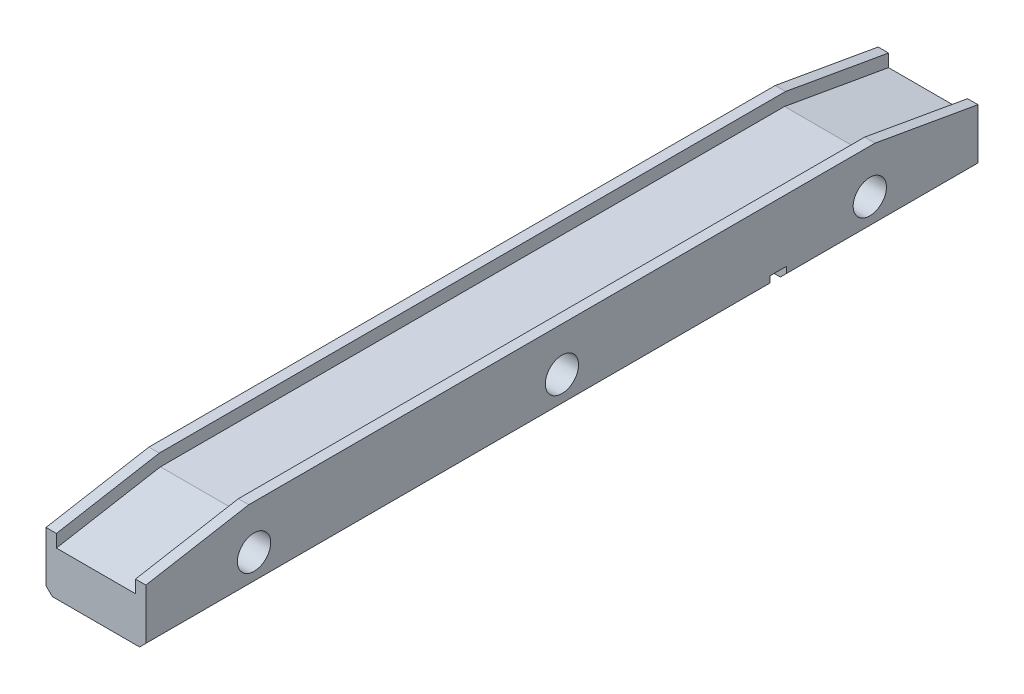
SolidWorks part; units mm, degrees
material "UHMW 15mm"
ref_plane "Plano frontal" through (0, 0, 0) normal (0, 0, 1) x (1, 0, 0)
ref_plane "Plano superior" through (0, 0, 0) normal (0, 1, 0) x (1, 0, 0)
ref_plane "Plano direito" through (0, 0, 0) normal (1, 0, 0) x (0, 0, -1)
sketch "Esboço1" plane through (0, 0, 0) normal (0, 0, 1) x (1, 0, 0)
  line L0 (-19, 0) -> (19, 0)
  line L1 (19, 0) -> (19, 6)
  line L2 (19, 6) -> (24, 6)
  line L3 (24, 6) -> (24, -30)
  line L4 (24, -30) -> (-24, -30)
  line L5 (0, -30) -> (0, 0) construction
  line L6 (-24, 6) -> (-24, -30)
  line L7 (-19, 6) -> (-24, 6)
  line L8 (-19, 0) -> (-19, 6)
  dimension "D1" = 38
  dimension "D2" = 48
  dimension "D3" = 6
  dimension "D4" = 30
extrude "Ressalto-extrusão1" add sketch "Esboço1" along normal mid plane 356
sketch "Esboço2" plane through (24, 0, 0) normal (1, 0, 0) x (0, 0, -1)
  line L0 (-178, -15) -> (178, -15) construction
  line L1 (-178, -30) -> (-178, 6) construction
  line L2 (178, -30) -> (178, 6) construction
  line L4 (-178, -36.6936) -> (-148, -36.6936) construction
  line L5 (-148, -36.6936) -> (-148, -15) construction
  line L6 (148, -15) -> (148, -36.6936) construction
  line L7 (148, -36.6936) -> (178, -36.6936) construction
  line L9 (-178, 0) -> (178, 0) construction
  circle A1 centre (-148, -15) radius 8
  circle A2 centre (148, -15) radius 8
  circle A3 centre (-128, -15) radius 8 construction
  dimension "D1" = 15
  dimension "D2" = 16
  dimension "D3" = 20
  dimension "D4" = 276
  dimension "D5" = 30
extrude "Corte-extrusão1" cut sketch "Esboço2" against normal blind 655
sketch "Esboço3" plane through (0, 0, 178) normal (0, 0, 1) x (1, 0, 0)
  line L8 (-24, 6) -> (-24, -30)
  line L9 (-24, -30) -> (24, -30)
  line L10 (24, -30) -> (24, 6)
  line L11 (24, 6) -> (19, 6)
  line L12 (19, 6) -> (19, 0)
  line L13 (19, 0) -> (-19, 0)
  line L14 (-19, 0) -> (-19, 6)
  line L15 (-19, 6) -> (-24, 6)
  line L16 (-24, 6) -> (-24, -30)
  line L17 (-24, -30) -> (24, -30)
  line L18 (24, -30) -> (24, 6)
  line L19 (24, 6) -> (19, 6)
  line L20 (19, 6) -> (19, 0)
  line L21 (19, 0) -> (-19, 0)
  line L22 (-19, 0) -> (-19, 6)
  line L23 (-19, 6) -> (-24, 6)
  dimension "D1" = 0
extrude "Ressalto-extrusão2" add sketch "Esboço3" along normal blind 22
sketch "Esboço4" plane through (0, 0, -178) normal (0, 0, -1) x (-1, 0, 0)
  line L8 (24, -30) -> (24, 6)
  line L9 (24, 6) -> (19, 6)
  line L10 (19, 6) -> (19, 0)
  line L11 (19, 0) -> (-19, 0)
  line L12 (-19, 0) -> (-19, 6)
  line L13 (-19, 6) -> (-24, 6)
  line L14 (-24, 6) -> (-24, -30)
  line L15 (-24, -30) -> (24, -30)
  line L16 (24, -30) -> (24, 6)
  line L17 (24, 6) -> (19, 6)
  line L18 (19, 6) -> (19, 0)
  line L19 (19, 0) -> (-19, 0)
  line L20 (-19, 0) -> (-19, 6)
  line L21 (-19, 6) -> (-24, 6)
  line L22 (-24, 6) -> (-24, -30)
  line L23 (-24, -30) -> (24, -30)
  dimension "D1" = 0
extrude "Ressalto-extrusão3" add sketch "Esboço4" along normal blind 22
sketch "Esboço5" plane through (24, 0, 0) normal (1, 0, 0) x (0, 0, -1)
  line L0 (-200, 6) -> (200, 6) construction
  line L1 (100, -24) -> (108, -24)
  line L2 (100, -24) -> (100, -56.977)
  line L3 (100, -56.977) -> (108, -56.977)
  line L4 (108, -24) -> (108, -56.977)
  circle A0 centre (148, -15) radius 8 construction
  dimension "D1" = 8
  dimension "D2" = 40
  dimension "D3" = 30
extrude "Corte-extrusão2" cut sketch "Esboço5" against normal blind 89
chamfer "Chanfro1" distance 50 angle 10 2 edges at (0, 0, -200) (0, 0, 200)
sketch "Esboço6" plane through (24, 0, 0) normal (1, 0, 0) x (0, 0, -1)
  line L1 (-135.212, 8.7001) -> (-200, 6)
  line L2 (-201.0419, -2.9075) -> (-151.0419, 5.9088)
  line L3 (-201.0419, -2.9075) -> (-135.212, 8.7001)
  line L4 (-200, 6) -> (-201.0419, -2.9075)
  line L5 (0, 0) -> (0, 47.1886) construction
  line L6 (200, 6) -> (201.0419, -2.9075)
  line L7 (201.0419, -2.9075) -> (135.212, 8.7001)
  line L8 (135.212, 8.7001) -> (200, 6)
  point P10 (-135.212, 8.7001)
  point P12 (-200, 6)
  dimension "D1" = 6
extrude "Corte-extrusão3" cut sketch "Esboço6" against normal blind 108
chamfer "Chanfro2" distance 3 angle 45 2 edges at (-24, -30, -154) (24, -30, -154)
sketch "Esboço7" plane through (24, 0, 0) normal (1, 0, 0) x (0, 0, -1)
  line L0 (148, -15) -> (-148, -15) construction
  circle A0 centre (0, -15) radius 8
  dimension "D1" = 16
extrude "Corte-extrusão4" cut sketch "Esboço7" against normal blind 89
